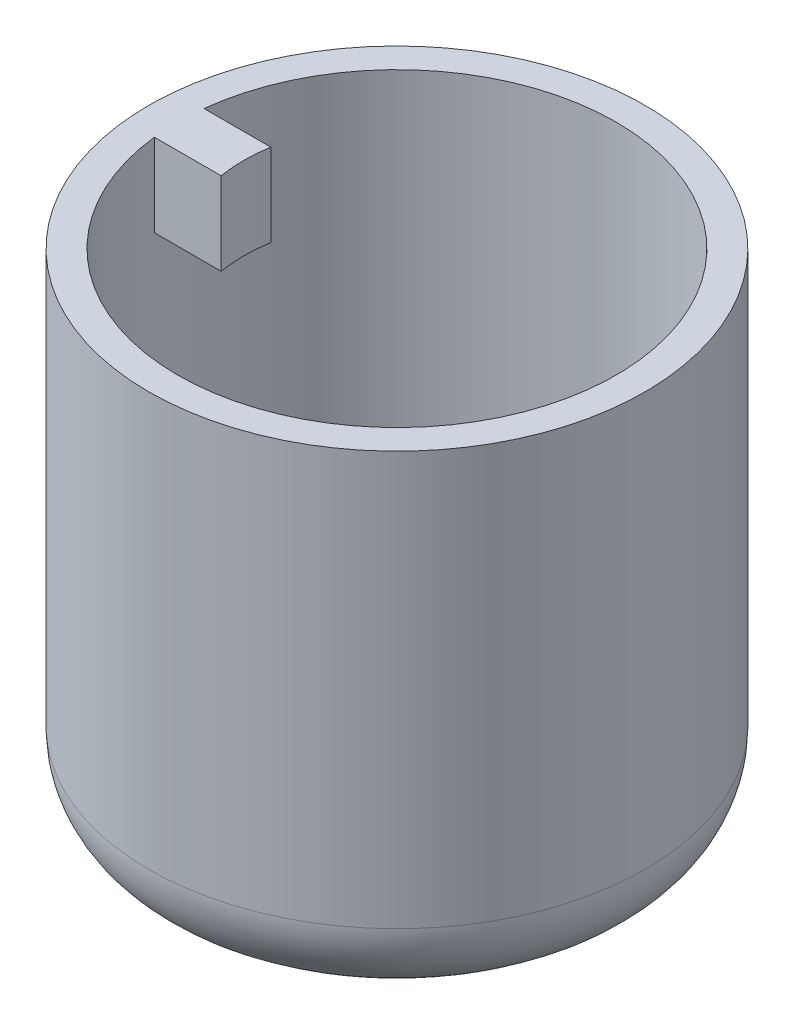
SolidWorks part; units mm, degrees
ref_plane "Piano frontale" through (0, 0, 0) normal (0, 0, 1) x (1, 0, 0)
ref_plane "Piano superiore" through (0, 0, 0) normal (0, 1, 0) x (1, 0, 0)
ref_plane "Piano destro" through (0, 0, 0) normal (1, 0, 0) x (0, 0, -1)
sketch "Schizzo1" plane through (0, 0, 0) normal (0, 1, 0) x (1, 0, 0)
  circle A1 centre (0, 0) radius 15
  dimension "D1" = 30
extrude "Estrusione-Estrusione1" add sketch "Schizzo1" along normal blind 30 contours A1
sketch "Schizzo3" plane through (0, 0, 0) normal (0, -1, 0) x (1, 0, 0)
  circle A0 centre (0, 0) radius 5.75
  dimension "D1" = 11.5
extrude "Taglio-Estrusione1" cut sketch "Schizzo3" against normal blind 2
sketch "Schizzo4" plane through (0, 2, 0) normal (0, -1, 0) x (1, 0, 0)
  circle A0 centre (0, 0) radius 13.25
  dimension "D1" = 26.5
extrude "Taglio-Estrusione2" cut sketch "Schizzo4" against normal through all
ref_plane "Piano1" through (0, 30, 0) normal (0, 1, 0) x (1, 0, 0)
sketch "Schizzo5" plane through (0, 30, 0) normal (0, 1, 0) x (1, 0, 0)
  line L0 (-13.1648, 1.5) -> (-9.1276, 1.5)
  line L1 (-16.5, 0) -> (16.5, 0) construction
  line L2 (-13.1648, -1.5) -> (-9.1276, -1.5)
  circle A0 centre (0, 0) radius 9.25 construction
  circle A1 centre (0, 0) radius 13.25 construction
  arc A2 (-9.1276, -1.5) -> (-9.1276, 1.5) centre (0, 0) cw
  arc A3 (-13.1648, 1.5) -> (-13.1648, -1.5) centre (0, 0) ccw
  dimension "D1" = 18.5
  dimension "D2" = 1.5
extrude "Estrusione-Estrusione2" add sketch "Schizzo5" against normal blind 5
fillet "Raccordo1" radius 5 1 edges at (0, 0, 15)
